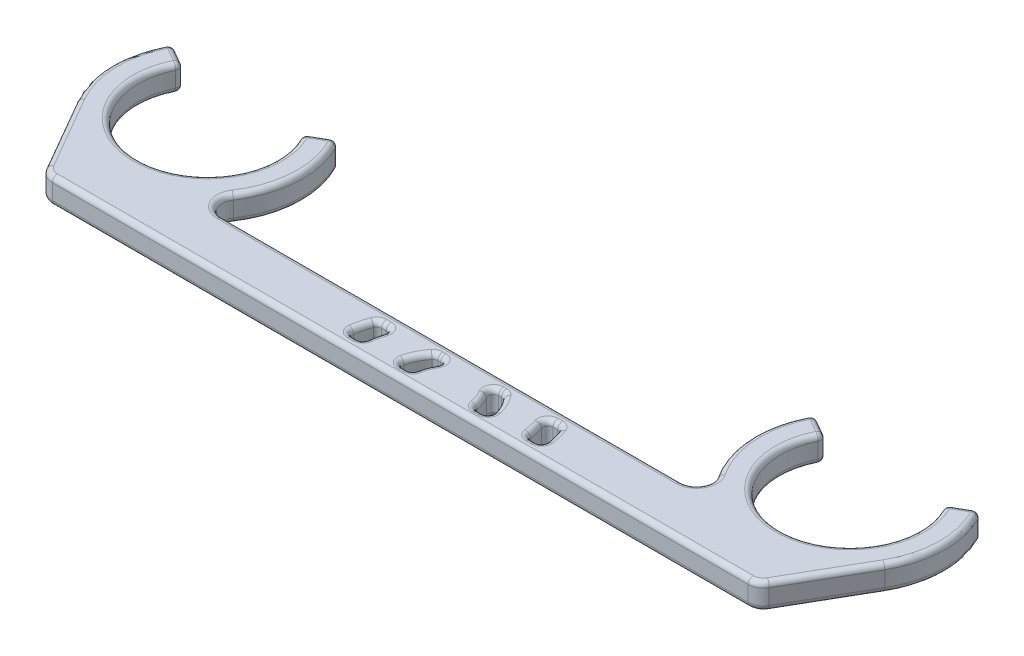
SolidWorks part; units mm, degrees
ref_plane "前视基准面" through (0, 0, 0) normal (0, 0, 1) x (1, 0, 0)
ref_plane "上视基准面" through (0, 0, 0) normal (0, 1, 0) x (1, 0, 0)
ref_plane "右视基准面" through (0, 0, 0) normal (1, 0, 0) x (0, 0, -1)
sketch "草图1" plane through (0, 0, 0) normal (0, 1, 0) x (1, 0, 0)
  line L0 (-11.6913, 6.75) -> (-16.0215, 9.25)
  line L1 (0, 0) -> (0, 32.2545) construction
  line L2 (11.6913, 6.75) -> (16.0215, 9.25)
  line L3 (-11.6913, 6.75) -> (0, 0) construction
  line L7 (0, 0) -> (62.5, 0) construction
  line L8 (62.5, 0) -> (62.5, 97.2449) construction
  line L12 (113.3087, 6.75) -> (108.9785, 9.25)
  line L13 (136.6913, 6.75) -> (141.0215, 9.25)
  line L16 (10.8282, -15) -> (114.1718, -15)
  line L18 (-6.9282, -25) -> (131.9282, -25)
  line L29 (62.5373, -22.738) -> (59.5373, -22.738)
  line L36 (58.5414, -26.5909) -> (68.5, -26.5909) construction
  line L37 (68.5, -26.5909) -> (68.5, -15) construction
  line L38 (53.6905, -17.5) -> (50.6905, -17.5)
  line L39 (61.8425, -17.5) -> (64.8425, -17.5)
  line L40 (75.1575, -17.5) -> (72.1575, -17.5)
  line L41 (74.4627, -22.738) -> (77.4627, -22.738)
  line L42 (49.5409, -22.4133) -> (52.5409, -22.4133)
  line L43 (83.3095, -17.5) -> (86.3095, -17.5)
  line L44 (87.4591, -22.4133) -> (84.4591, -22.4133)
  line L45 (131.9282, -25) -> (141.0215, -9.25)
  line L46 (62.5, -15) -> (62.5, -10.2619) construction
  line L2669 (-6.9282, -25) -> (-16.0215, -9.25)
  arc A0 (-11.6913, 6.75) -> (11.6913, 6.75) centre (0, 0) ccw
  arc A1 (-16.0215, 9.25) -> (-16.0215, -9.25) centre (0, 0) ccw
  arc A2 (136.6913, 6.75) -> (113.3087, 6.75) centre (125, 0) cw
  arc A3 (141.0215, 9.25) -> (141.0215, -9.25) centre (125, 0) cw
  arc A4 (114.1718, -15) -> (108.9785, 9.25) centre (125, 0) cw
  arc A5 (10.8282, -15) -> (16.0215, 9.25) centre (0, 0) ccw
  arc A6 (61.8425, -17.5) -> (59.5373, -22.738) centre (68.5, -23.5562) ccw
  arc A7 (53.6905, -17.5) -> (52.5409, -22.4133) centre (68.5, -23.5562) ccw
  arc A8 (64.8425, -17.5) -> (62.5373, -22.738) centre (71.5, -23.5562) ccw
  arc A12 (50.6905, -17.5) -> (49.5409, -22.4133) centre (65.5, -23.5562) ccw
  arc A13 (72.1575, -17.5) -> (74.4627, -22.738) centre (65.5, -23.5562) cw
  arc A15 (75.1575, -17.5) -> (77.4627, -22.738) centre (68.5, -23.5562) cw
  arc A16 (86.3095, -17.5) -> (87.4591, -22.4133) centre (71.5, -23.5562) cw
  arc A17 (83.3095, -17.5) -> (84.4591, -22.4133) centre (68.5, -23.5562) cw
  point P14 (63.8415, -15.8556)
  point P24 (55.3583, -14.4296)
  dimension "D1" = 27
  dimension "D2" = 37
  dimension "D5" = 125
  dimension "D7" = 9
  dimension "D17" = 16
  dimension "D3" = 60
  dimension "D4" = 10
  dimension "D6" = 15
  dimension "D8" = 1.4438
  dimension "D9" = 2.5
  dimension "D10" = 2
  dimension "D11" = 6
  dimension "D12" = 3
  dimension "D13" = 2
  dimension "D14" = 120
  dimension "D15" = 2.262
  dimension "D16" = 2.5867
extrude "凸台-拉伸1" add sketch "草图1" along normal blind 5
fillet "圆角1" radius 3 4 edges at (114.1718, 2.5, 15) (10.8282, 2.5, 15) (131.9282, 2.5, 25) (-6.9282, 2.5, 25)
fillet "圆角2" radius 1 24 edges at (83.3095, 2.5, 17.5) (84.4591, 2.5, 22.4133) (87.4591, 2.5, 22.4133) (86.3095, 2.5, 17.5) (72.1575, 2.5, 17.5) (74.4627, 2.5, 22.738) (77.4627, 2.5, 22.738) (75.1575, 2.5, 17.5) (62.5373, 2.5, 22.738) (64.8425, 2.5, 17.5) (59.5373, 2.5, 22.738) (-16.0215, 2.5, -9.25) (-11.6913, 2.5, -6.75) (11.6913, 2.5, -6.75) (16.0215, 2.5, -9.25) (108.9785, 2.5, -9.25) (113.3087, 2.5, -6.75) (136.6913, 2.5, -6.75) (141.0215, 2.5, -9.25) (61.8425, 2.5, 17.5) (49.5409, 2.5, 22.4133) (52.5409, 2.5, 22.4133) (50.6905, 2.5, 17.5) (53.6905, 2.5, 17.5)
fillet "圆角3" radius 1 116 edges at (83.9253, 0, 17.9073) (85.1764, 0, 17.5) (86.1979, 0, 17.6824) (87.0277, 0, 19.6973) (87.1021, 0, 22.068) (85.8553, 0, 22.4133) (84.7034, 0, 22.1637) (73.2599, 0, 18.0028) (74.4136, 0, 17.5) (75.1285, 0, 17.5967) (76.5775, 0, 19.5871) (77.074, 0, 22.3596) (75.812, 0, 22.738) (74.6937, 0, 22.5067) (61.8715, 0, 17.5967) (62.5864, 0, 17.5) (63.7401, 0, 18.0028) (63.0658, 0, 20.4155) (62.3063, 0, 22.5067) (61.188, 0, 22.738) (59.926, 0, 22.3596) (50.8021, 0, 17.6824) (51.8236, 0, 17.5) (53.0747, 0, 17.9073) (52.8656, 0, 20.1553) (52.2966, 0, 22.1637) (51.1447, 0, 22.4133) (49.8979, 0, 22.068) (0, 0, 13.5) (84.1344, 0, 20.1553) (73.9342, 0, 20.4155) (60.4225, 0, 19.5871) (49.9723, 0, 19.6973) (15.1916, 0, 13.4101) (18.4635, 0, 1.1621) (-12.071, 0, -6.6587) (-15.917, 0, -8.8278) (-13.8291, 0, -7.9842) (12.071, 0, -6.6587) (15.917, 0, -8.8278) (13.8291, 0, -7.9842) (62.5, 0, 15) (109.8084, 0, 13.4101) (106.5365, 0, 1.1621) (112.929, 0, -6.6587) (111.1709, 0, -7.9842) (109.083, 0, -8.8278) (125, 0, 13.5) (137.071, 0, -6.6587) (140.917, 0, -8.8278) (138.8291, 0, -7.9842) (143.4924, 0, 0.5288) (136.9078, 0, 16.375) (131.6962, 0, 24.5981) (62.5, 0, 25) (-6.6962, 0, 24.5981) (-18.4924, 0, 0.5288) (-11.9078, 0, 16.375) (83.9253, 5, 17.9073) (84.1344, 5, 20.1553) (84.7034, 5, 22.1637) (85.8553, 5, 22.4133) (87.1021, 5, 22.068) (87.0277, 5, 19.6973) (86.1979, 5, 17.6824) (85.1764, 5, 17.5) (73.2599, 5, 18.0028) (73.9342, 5, 20.4155) (74.6937, 5, 22.5067) (75.812, 5, 22.738) (77.074, 5, 22.3596) (76.5775, 5, 19.5871) (75.1285, 5, 17.5967) (74.4136, 5, 17.5) (50.8021, 5, 17.6824) (49.9723, 5, 19.6973) (49.8979, 5, 22.068) (51.1447, 5, 22.4133) (52.2966, 5, 22.1637) (52.8656, 5, 20.1553) (53.0747, 5, 17.9073) (51.8236, 5, 17.5) (62.3063, 5, 22.5067) (63.0658, 5, 20.4155) (63.7401, 5, 18.0028) (62.5864, 5, 17.5) (61.8715, 5, 17.5967) (60.4225, 5, 19.5871) (59.926, 5, 22.3596) (61.188, 5, 22.738) (-12.071, 5, -6.6587) (0, 5, 13.5) (12.071, 5, -6.6587) (13.8291, 5, -7.9842) (15.917, 5, -8.8278) (18.4635, 5, 1.1621) (15.1916, 5, 13.4101) (62.5, 5, 15) (109.8084, 5, 13.4101) (106.5365, 5, 1.1621) (109.083, 5, -8.8278) (111.1709, 5, -7.9842) (112.929, 5, -6.6587) (125, 5, 13.5) (137.071, 5, -6.6587) (138.8291, 5, -7.9842) (140.917, 5, -8.8278) (143.4924, 5, 0.5288) (136.9078, 5, 16.375) (131.6962, 5, 24.5981) (62.5, 5, 25) (-6.6962, 5, 24.5981) (-11.9078, 5, 16.375) (-18.4924, 5, 0.5288) (-15.917, 5, -8.8278) (-13.8291, 5, -7.9842)
move or copy body "实体-移动/复制1" [suppressed] bodies to move or copy 106
